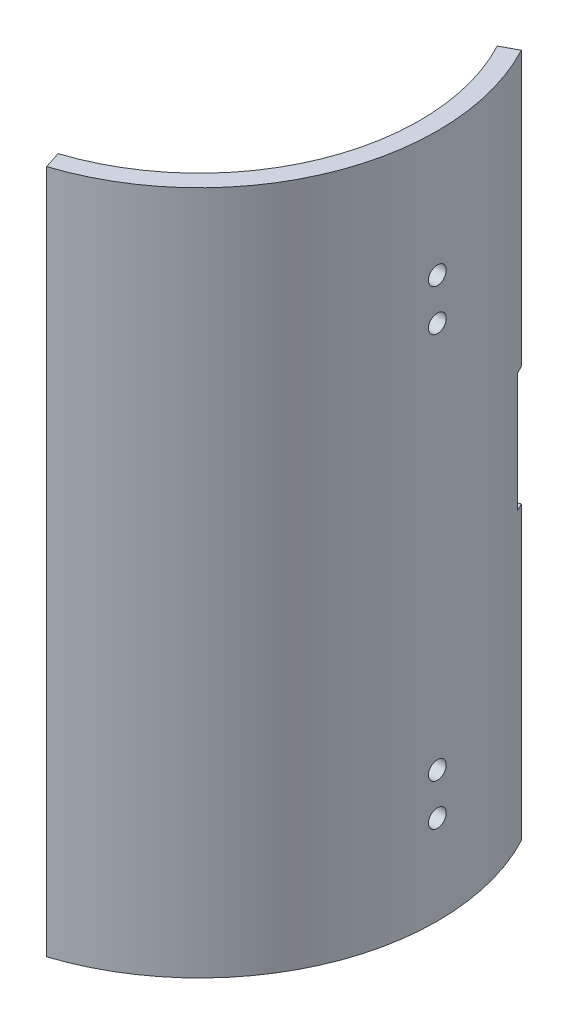
SolidWorks part; units mm, degrees
ref_plane "Plan de face" through (0, 0, 0) normal (0, 0, 1) x (1, 0, 0)
ref_plane "Plan de dessus" through (0, 0, 0) normal (0, 1, 0) x (1, 0, 0)
ref_plane "Plan de droite" through (0, 0, 0) normal (1, 0, 0) x (0, 0, -1)
sketch "Esquisse5" plane through (0, 0, 0) normal (0, 1, 0) x (1, 0, 0)
  line L0 (0, 0) -> (11.4336, -35.1891) construction
  line L1 (0, 0) -> (0, -35.1891) construction
  line L2 (32.6691, 17.3704) -> (35.3179, 18.7789)
  line L3 (11.4336, -35.1891) -> (12.3607, -38.0423)
  line L4 (0, -35.1891) -> (11.4336, -35.1891) construction
  arc A0 (35.3179, 18.7789) -> (12.3607, -38.0423) centre (0, 0) cw
  arc A2 (32.6691, 17.3704) -> (11.4336, -35.1891) centre (0, 0) cw
extrude "Extrusion1" add sketch "Esquisse5" along normal blind 115
sketch "Esquisse6" plane through (0, 0, 0) normal (1, 0, 0) x (0, 0, -1)
  line L0 (0, 0) -> (0, 120) construction
  line L1 (18.7789, 115) -> (-38.0423, 115) construction
  line L2 (17.3704, 115) -> (-35.1891, 115) construction
  line L3 (17.5, 69) -> (27.3227, 69)
  line L4 (17.5, 69) -> (17.5, 49)
  line L5 (17.5, 49) -> (27.3227, 49)
  line L6 (27.3227, 69) -> (27.3227, 49)
  circle A0 centre (0, 94) radius 1.5
  circle A1 centre (0, 87) radius 1.5
  circle A3 centre (0, 15) radius 1.5
  circle A4 centre (0, 22) radius 1.5
  dimension "D1" = 21
  dimension "D5" = 46
  dimension "D2" = 7
  dimension "D3" = 72
  dimension "D4" = 7
  dimension "D6" = 17.5
  dimension "D7" = 20
extrude "Extrusion4" cut sketch "Esquisse6" along normal through all
